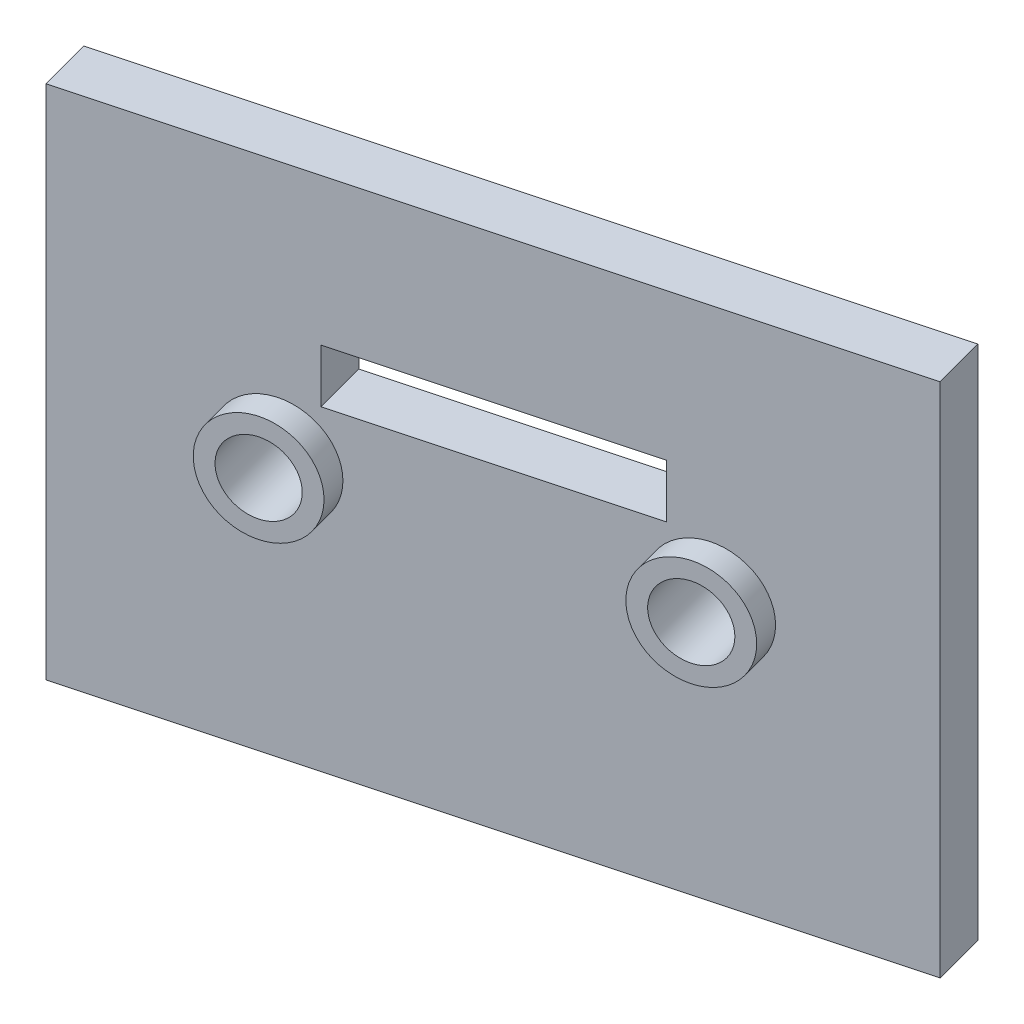
SolidWorks part; units mm, degrees
ref_plane "Front" through (0, 0, 0) normal (0, 0, 1) x (1, 0, 0)
ref_plane "Top" through (0, 0, 0) normal (0, 1, 0) x (1, 0, 0)
ref_plane "Right" through (0, 0, 0) normal (1, 0, 0) x (0, 0, -1)
sketch "Sketch1" plane through (0, 0, 0) normal (0, 0, 1) x (1, 0, 0)
  line L1 (-20.5, 14.5) -> (20.5, 14.5)
  line L2 (-20.5, 14.5) -> (-20.5, -14.5)
  line L3 (-20.5, -14.5) -> (20.5, -14.5)
  line L4 (20.5, 14.5) -> (20.5, -14.5)
  line L5 (-20.5, 14.5) -> (20.5, -14.5) construction
  line L6 (-20.5, -14.5) -> (20.5, 14.5) construction
  point P0 (0, 0)
  dimension "D1" = 41
  dimension "D2" = 29
extrude "Boss-Extrude1" add sketch "Sketch1" along normal blind 3
move or copy body "Body-Move/Copy1" bodies to move or copy 101 copy no translate (0.5, 0.5, 0)
sketch "Sketch11" plane through (0, 0, 3) normal (0, 0, 1) x (1, 0, 0)
  circle A0 centre (-9.3872, 0.5) radius 3
  circle A1 centre (10.4529, 0.5) radius 3
  point P0 (-9.3872, 0.5)
  point P1 (10.4529, 0.5)
  dimension "D1" = 6
  dimension "D2" = 6
extrude "Boss-Extrude2" add sketch "Sketch11" along normal blind 1.5
hole_wizard "Ø4.0 (4) Diameter Hole1" positions "Sketch14" profile "Sketch15" hole size "Ø4.0" standard "ANSI Metric" end condition up to next
sketch "Sketch14" plane through (0, 0, 4.5) normal (0, 0, 1) x (1, 0, 0)
  point P0 (-9.3872, 0.5)
  point P3 (10.4529, 0.5)
sketch "Sketch15" plane through (-9.3872, 0.5, 4.5) normal (1, 0, 0) x (0, -1, 0)
  line L0 (0, 0) -> (0, 4.5)
  line L1 (0, 4.5) -> (2, 4.5)
  line L2 (2, 4.5) -> (2, 0)
  line L5 (2, 0) -> (0, 0)
  line L11 (0, -6.35) -> (0, 107.95) construction
  dimension "Thru Hole Dia." = 4
  dimension "Thru Hole Depth" = 4.5
move or copy body "Body-Move/Copy8" bodies to move or copy 104 copy no translate (27.7957, 0, 0)
move or copy body "Body-Move/Copy9" bodies to move or copy 113 copy no rotation origin (28.2957, 0, 2.25) rotation axis (0, 1, 0) rotation angle 15
sketch "Sketch16" plane through (1.8756, 0, 6.9999) normal (-0.2588, 0, -0.9659) x (-0.9659, 0, 0.2588)
  line L1 (-34.7021, 0.5) -> (-18.862, 0.5)
  line L2 (-34.7021, 0.5) -> (-34.7021, 13)
  line L3 (-34.7021, 13) -> (-18.862, 13)
  line L4 (-18.862, 0.5) -> (-18.862, 13)
  circle A0 centre (-36.7021, 0.5) radius 2 construction
  dimension "D1" = 12.5
  dimension "D2" = 15.8402
extrude "Boss-Extrude3" add sketch "Sketch16" along normal blind 1 separate body
move or copy body "Body-Move/Copy10" bodies to move or copy 115 copy no translate (0, -6.25, 0)
sketch "Sketch17" plane through (1.6168, 0, 6.0339) normal (-0.2588, 0, -0.9659) x (-0.9659, 0, 0.2588)
  line L0 (-18.862, -5.75) -> (-18.862, 6.75) construction
  line L1 (-34.7021, 6.75) -> (-18.862, 6.75)
  line L2 (-34.7021, 6.75) -> (-34.7021, 3.75)
  line L3 (-34.7021, 3.75) -> (-18.862, 3.75)
  line L4 (-18.862, 6.75) -> (-18.862, 3.75)
  dimension "D1" = 3
extrude "Boss-Extrude4" add sketch "Sketch17" against normal blind 20 separate body
combine bodies "Combine1" operation type subtract main body 114 bodies to subtract 116 117
